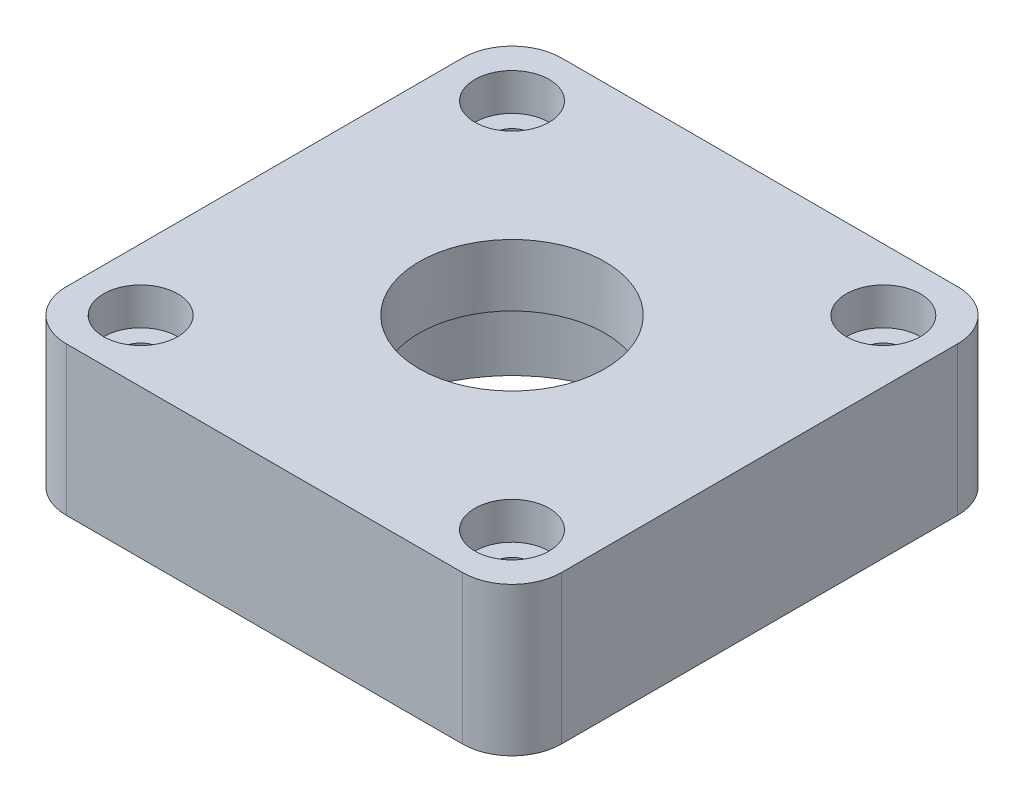
SolidWorks part; units mm, degrees
ref_plane "Front Plane" through (0, 0, 0) normal (0, 0, 1) x (1, 0, 0)
ref_plane "Top Plane" through (0, 0, 0) normal (0, 1, 0) x (1, 0, 0)
ref_plane "Right Plane" through (0, 0, 0) normal (1, 0, 0) x (0, 0, -1)
sketch "Sketch1" plane through (0, 0, 0) normal (0, 1, 0) x (1, 0, 0)
  line L1 (-20, 20) -> (20, 20)
  line L2 (-20, 20) -> (-20, -20)
  line L3 (-20, -20) -> (20, -20)
  line L4 (20, 20) -> (20, -20)
  line L5 (-20, 20) -> (20, -20) construction
  line L6 (-20, -20) -> (20, 20) construction
  point P0 (0, 0)
  dimension "D1" = 40
extrude "Boss-Extrude1" add sketch "Sketch1" along normal blind 12
sketch "Sketch2" plane through (0, 0, 0) normal (0, -1, 0) x (1, 0, 0)
  circle A0 centre (0, 0) radius 11
  dimension "D1" = 22
extrude "Cut-Extrude1" cut sketch "Sketch2" against normal blind 7
sketch "Sketch3" plane through (0, 12, 0) normal (0, 1, 0) x (1, 0, 0)
  circle A0 centre (0, 0) radius 7.5
  dimension "D1" = 15
extrude "Cut-Extrude2" cut sketch "Sketch3" against normal through all
fillet "Fillet1" radius 4 4 edges at (20, 6, -20) (-20, 6, -20) (-20, 6, 20) (20, 6, 20)
sketch "Sketch4" plane through (0, 12, 0) normal (0, 1, 0) x (1, 0, 0)
  line L0 (-20, 16) -> (-20, -16) construction
  line L1 (16, 20) -> (-16, 20) construction
  line L2 (0, 20) -> (0, -20) construction
  line L3 (-16, -20) -> (16, -20) construction
  line L4 (-20, 0) -> (20, 0) construction
  line L5 (20, -16) -> (20, 16) construction
  circle A0 centre (-15, 15) radius 1.5
  circle A1 centre (15, 15) radius 1.5
  circle A2 centre (15, -15) radius 1.5
  circle A3 centre (-15, -15) radius 1.5
  dimension "D1" = 3
  dimension "D2" = 5
  dimension "D3" = 5
extrude "Cut-Extrude3" cut sketch "Sketch4" against normal through all
sketch "Sketch5" plane through (0, 12, 0) normal (0, 1, 0) x (1, 0, 0)
  line L0 (0, -20) -> (0, 20) construction
  line L1 (-16, -20) -> (16, -20) construction
  line L2 (16, 20) -> (-16, 20) construction
  line L3 (-20, 0) -> (20, 0) construction
  line L4 (-20, 16) -> (-20, -16) construction
  line L5 (20, -16) -> (20, 16) construction
  circle A0 centre (-15, -15) radius 3
  circle A1 centre (-15, 15) radius 3
  circle A2 centre (15, -15) radius 3
  circle A3 centre (15, 15) radius 3
  point P14 (0, 0)
  dimension "D1" = 6
extrude "Cut-Extrude4" cut sketch "Sketch5" against normal blind 3
